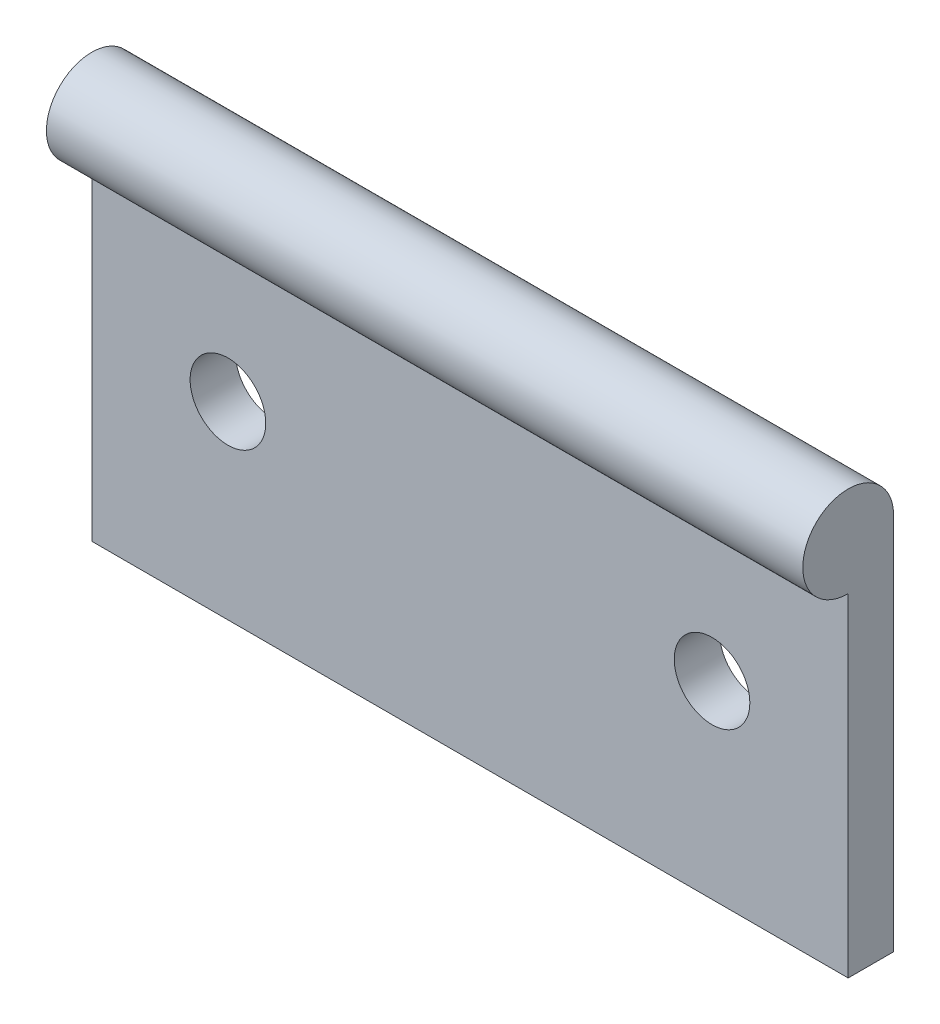
SolidWorks part; units mm, degrees
ref_plane "Plan de face" through (0, 0, 0) normal (0, 0, 1) x (1, 0, 0)
ref_plane "Plan de dessus" through (0, 0, 0) normal (0, 1, 0) x (1, 0, 0)
ref_plane "Plan de droite" through (0, 0, 0) normal (1, 0, 0) x (0, 0, -1)
sketch "Esquisse1" plane through (0, 0, 0) normal (0, 0, 1) x (1, 0, 0)
  line L1 (-25, 12.5) -> (25, 12.5)
  line L2 (-25, 12.5) -> (-25, -12.5)
  line L3 (-25, -12.5) -> (25, -12.5)
  line L4 (25, 12.5) -> (25, -12.5)
  line L5 (-25, 12.5) -> (25, -12.5) construction
  line L6 (-25, -12.5) -> (25, 12.5) construction
  point P0 (0, 0)
  dimension "D1" = 25
  dimension "D2" = 50
extrude "Boss.-Extru.1" add sketch "Esquisse1" along normal blind 3
sketch "Esquisse2" plane through (0, 0, 0) normal (1, 0, 0) x (0, 0, -1)
  line L0 (0, -12.5) -> (0, 12.5) construction
  circle A0 centre (-3, 12.5) radius 3
extrude "Boss.-Extru.2" add sketch "Esquisse2" along normal mid plane 50
sketch "Esquisse3" plane through (0, 0, 3) normal (0, 0, 1) x (1, 0, 0)
  line L0 (-16, 0) -> (16, 0) construction
  circle A0 centre (-16, 0) radius 2.5
  circle A1 centre (16, 0) radius 2.5
  point P4 (0, 0)
  dimension "D2" = 5
  dimension "D1" = 32
extrude "Enlèv. mat.-Extru.1" cut sketch "Esquisse3" against normal through all
